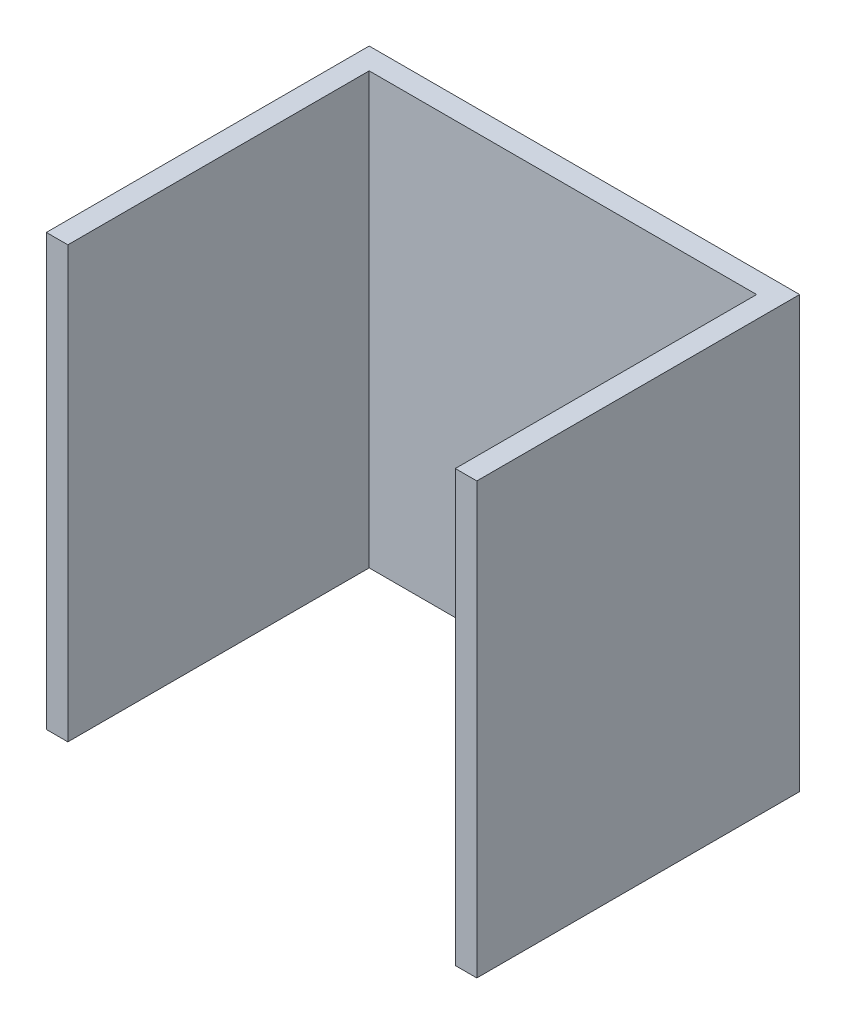
SolidWorks part; units mm, degrees
ref_plane "Front Plane" through (0, 0, 0) normal (0, 0, 1) x (1, 0, 0)
ref_plane "Top Plane" through (0, 0, 0) normal (0, 1, 0) x (1, 0, 0)
ref_plane "Right Plane" through (0, 0, 0) normal (1, 0, 0) x (0, 0, -1)
sketch "Sketch1" plane through (0, 0, 0) normal (0, 0, 1) x (1, 0, 0)
  line L1 (-50, -50) -> (50, -50)
  line L2 (-50, -50) -> (-50, 50)
  line L3 (-50, 50) -> (50, 50)
  line L4 (50, -50) -> (50, 50)
  line L5 (-50, -50) -> (50, 50) construction
  line L6 (-50, 50) -> (50, -50) construction
  line L7 (-50, 50) -> (-45, 50)
  line L8 (-50, 50) -> (-50, -50)
  line L9 (-50, -50) -> (-45, -50)
  line L10 (-45, 50) -> (-45, -50)
  line L11 (50, 50) -> (45, 50)
  line L12 (50, 50) -> (50, -50)
  line L13 (50, -50) -> (45, -50)
  line L14 (45, 50) -> (45, -50)
  point P0 (0, 0)
  dimension "D1" = 100
  dimension "D2" = 100
  dimension "D3" = 5
  dimension "D4" = 5
extrude "Boss-Extrude1" add sketch "Sketch1" against normal blind 5 contours L2 L3 L4 L1
sketch "Sketch2" plane through (0, 0, 0) normal (0, 0, 1) x (1, 0, 0)
  line L0 (-50, -50) -> (50, -50) construction
  line L1 (-50, 50) -> (-45, 50)
  line L2 (-50, 50) -> (-50, -50)
  line L3 (-50, -50) -> (-45, -50)
  line L4 (-45, 50) -> (-45, -50)
  line L6 (50, 50) -> (45, 50)
  line L7 (50, 50) -> (50, -50)
  line L8 (50, -50) -> (45, -50)
  line L9 (45, 50) -> (45, -50)
  dimension "D1" = 5
  dimension "D2" = 5
extrude "Boss-Extrude3" add sketch "Sketch2" along normal blind 70
